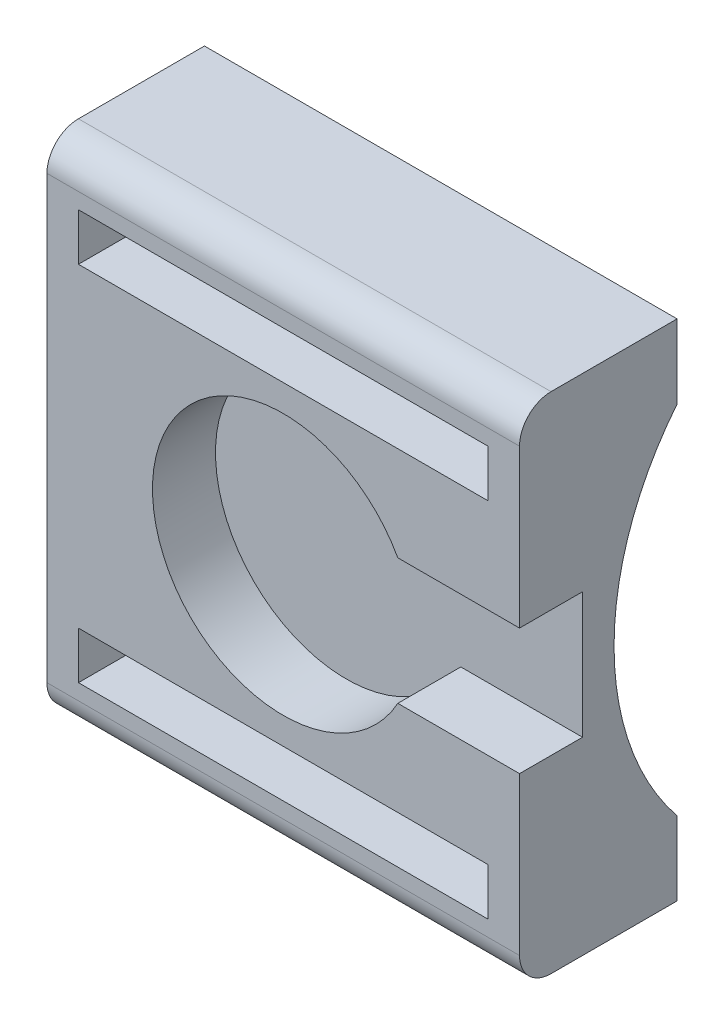
SolidWorks part; units mm, degrees
ref_plane "Front Plane" through (0, 0, 0) normal (0, 0, 1) x (1, 0, 0)
ref_plane "Top Plane" through (0, 0, 0) normal (0, 1, 0) x (1, 0, 0)
ref_plane "Right Plane" through (0, 0, 0) normal (1, 0, 0) x (0, 0, -1)
sketch "Sketch1" plane through (0, 0, 0) normal (0, 0, 1) x (1, 0, 0)
  line L1 (-7.5, 8) -> (7.5, 8)
  line L2 (-7.5, 8) -> (-7.5, -8)
  line L3 (-7.5, -8) -> (7.5, -8)
  line L4 (7.5, 8) -> (7.5, -8)
  line L5 (-7.5, 8) -> (7.5, -8) construction
  line L6 (-7.5, -8) -> (7.5, 8) construction
  point P0 (0, 0)
  dimension "D1" = 15
  dimension "D2" = 16
extrude "Boss-Extrude1" add sketch "Sketch1" along normal blind 5
sketch "Sketch2" plane through (0, 0, 5) normal (0, 0, 1) x (1, 0, 0)
  circle A0 centre (0, 0) radius 4.15
  dimension "D1" = 8.3
extrude "Cut-Extrude1" cut sketch "Sketch2" against normal blind 2
sketch "Sketch4" plane through (7.5, 0, 0) normal (1, 0, 0) x (0, 0, -1)
  line L0 (-5, -8) -> (-5, 8) construction
  line L1 (-7, 2) -> (-3, 2)
  line L2 (-7, 2) -> (-7, -2)
  line L3 (-7, -2) -> (-3, -2)
  line L4 (-3, 2) -> (-3, -2)
  line L5 (-7, 2) -> (-3, -2) construction
  line L6 (-7, -2) -> (-3, 2) construction
  point P0 (-5, 0)
  dimension "D1" = 4
  dimension "D2" = 4
extrude "Cut-Extrude2" cut sketch "Sketch4" against normal blind 4
sketch "Sketch8" plane through (0, 0, 5) normal (0, 0, 1) x (1, 0, 0)
  line L1 (-6.5, 6.5) -> (6.5, 6.5)
  line L2 (-6.5, 6.5) -> (-6.5, 5)
  line L3 (-6.5, 5) -> (6.5, 5)
  line L4 (6.5, 6.5) -> (6.5, 5)
  line L5 (-6.5, -5) -> (6.5, -5)
  line L6 (-6.5, -5) -> (-6.5, -6.5)
  line L7 (-6.5, -6.5) -> (6.5, -6.5)
  line L8 (6.5, -5) -> (6.5, -6.5)
  line L9 (-7.5, 8) -> (-7.5, -8) construction
  line L10 (7.5, 2) -> (7.5, 8) construction
  line L11 (7.5, -8) -> (7.5, -2) construction
  dimension "D1" = 5
  dimension "D2" = 1
  dimension "D3" = 1
  dimension "D4" = 1.5
  dimension "D5" = 1
  dimension "D6" = 1
  dimension "D7" = 5
  dimension "D8" = 1.5
extrude "Cut-Extrude4" cut sketch "Sketch8" against normal blind 10
sketch "Sketch9" plane through (-7.5, 0, 0) normal (-1, 0, 0) x (0, 0, 1)
  line L0 (0, 8) -> (0, -8) construction
  circle A0 centre (-7, 0) radius 9
  dimension "D1" = 18
  dimension "D2" = 7
extrude "Cut-Extrude6" cut sketch "Sketch9" against normal blind 50
fillet "Fillet2" radius 1 1 edges at (0, 8, 5)
fillet "Fillet3" radius 1 1 edges at (0, -8, 5)
